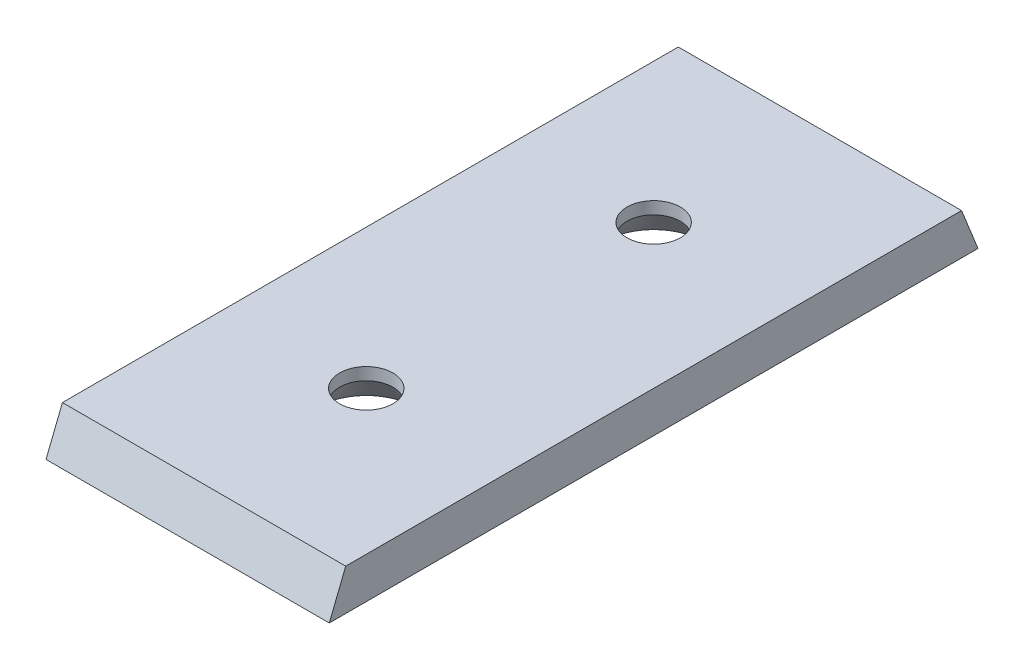
SolidWorks part; units mm, degrees
ref_plane "前视基准面" through (0, 0, 0) normal (0, 0, 1) x (1, 0, 0)
ref_plane "上视基准面" through (0, 0, 0) normal (0, 1, 0) x (1, 0, 0)
ref_plane "右视基准面" through (0, 0, 0) normal (1, 0, 0) x (0, 0, -1)
sketch "草图1" plane through (0, 0, 0) normal (0, 1, 0) x (1, 0, 0)
  line L0 (0, 0) -> (-53.9344, 0) construction
  line L1 (-34.5, 79) -> (34.5, 79)
  line L2 (-34.5, 79) -> (-34.5, -79)
  line L3 (-34.5, -79) -> (34.5, -79)
  line L4 (34.5, 79) -> (34.5, -79)
  line L5 (0, 0) -> (0, 111.8446) construction
  dimension "D1" = 158
  dimension "D2" = 69
extrude "凸台-拉伸1" add sketch "草图1" along normal blind 10
sketch "草图4" plane through (0, 0, 0) normal (0, -1, 0) x (1, 0, 0)
  line L0 (34.5, 79) -> (34.5, -79) construction
  circle A0 centre (-0.5, 35) radius 6.5
  dimension "D1" = 13
  dimension "D2" = 35
  dimension "D3" = 35
extrude "切除-拉伸2" cut sketch "草图4" against normal up to next
chamfer "倒角1" distance 5.5 distance2 7 1 edges at (-0.5, 0, 28.5)
pattern_linear "阵列(线性)2" count 2 spacing 70 along (0, 0, -1) of "切除-拉伸2", "倒角1"
sketch "草图6" plane through (34.5, 0, 0) normal (1, 0, 0) x (0, 0, -1)
  line L0 (-79, 0) -> (-75.0003, 10)
  line L4 (-79, 10) -> (79, 10) construction
  line L5 (-75.0003, 10) -> (-79, 10)
  line L6 (-79, 10) -> (-79, 0)
  line L7 (-79, 0) -> (79, 0) construction
  line L8 (0, 5.5) -> (0, -5.5) construction
  line L9 (79, 10) -> (79, 0)
  line L10 (75.0003, 10) -> (79, 10)
  line L11 (79, 0) -> (75.0003, 10)
  dimension "D1" = 68.2
extrude "切除-拉伸3" cut sketch "草图6" against normal up to next
